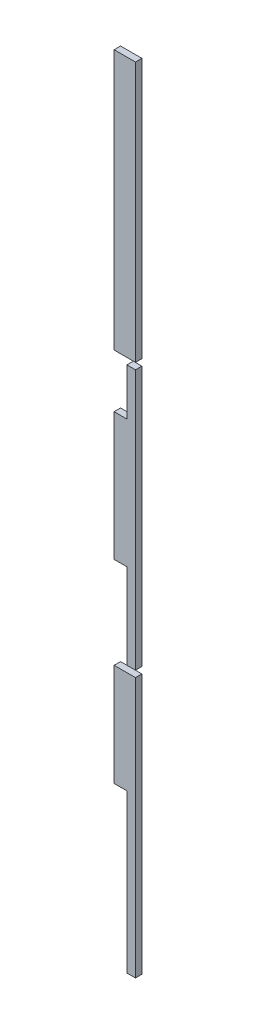
SolidWorks part; units mm, degrees
material "轻木"
ref_plane "前视基准面" through (0, 0, 0) normal (0, 0, 1) x (1, 0, 0)
ref_plane "上视基准面" through (0, 0, 0) normal (0, 1, 0) x (1, 0, 0)
ref_plane "右视基准面" through (0, 0, 0) normal (1, 0, 0) x (0, 0, -1)
other "Configuration Table"
sketch "草图1" plane through (0, 0, 0) normal (0, 0, 1) x (1, 0, 0)
  line L0 (130.7876, -890.01) -> (-44.1255, -890.01) construction
  line L1 (120.7876, -768.01) -> (130.7876, -768.01)
  line L2 (120.7876, -768.01) -> (120.7876, -890.01)
  line L3 (120.7876, -890.01) -> (130.7876, -890.01)
  line L4 (130.7876, -768.01) -> (130.7876, -890.01)
  line L5 (130.7876, -1068.01) -> (130.7876, -768.01) construction
  line L7 (120.7876, -975.01) -> (126.7876, -975.01)
  line L8 (120.7876, -975.01) -> (120.7876, -915.01)
  line L9 (120.7876, -915.01) -> (126.7876, -915.01)
  line L10 (130.7876, -985.01) -> (130.7876, -925.01)
  line L11 (120.7876, -893.01) -> (120.7876, -1015.01) construction
  line L12 (130.7876, -1015.01) -> (-44.1255, -1015.01) construction
  line L13 (130.7876, -1140.01) -> (-44.1255, -1140.01) construction
  line L14 (120.7876, -1018.01) -> (130.7876, -1018.01)
  line L15 (120.7876, -1018.01) -> (120.7876, -1066.01)
  line L16 (120.7876, -1066.01) -> (126.7876, -1066.01)
  line L17 (130.7876, -1018.01) -> (130.7876, -1076.01)
  line L19 (130.7876, -1076.01) -> (130.7876, -1140.01)
  line L20 (130.7876, -1140.01) -> (126.7876, -1140.01)
  line L21 (126.7876, -1066.01) -> (126.7876, -1140.01)
  line L24 (130.7876, -985.01) -> (130.7876, -1015.01)
  line L25 (130.7876, -1015.01) -> (126.7876, -1015.01)
  line L26 (126.7876, -975.01) -> (126.7876, -1015.01)
  line L27 (130.7876, -893.01) -> (126.7876, -893.01)
  line L28 (130.7876, -893.01) -> (130.7876, -925.01)
  line L30 (126.7876, -893.01) -> (126.7876, -915.01)
  dimension "D1" = 60
  dimension "D2" = 40
  dimension "D3" = 4
  dimension "D5" = 48
  dimension "D6" = 10
  dimension "D7" = 4
  dimension "D8" = 4
extrude "凸台-拉伸1" add sketch "草图1" along normal blind 3
